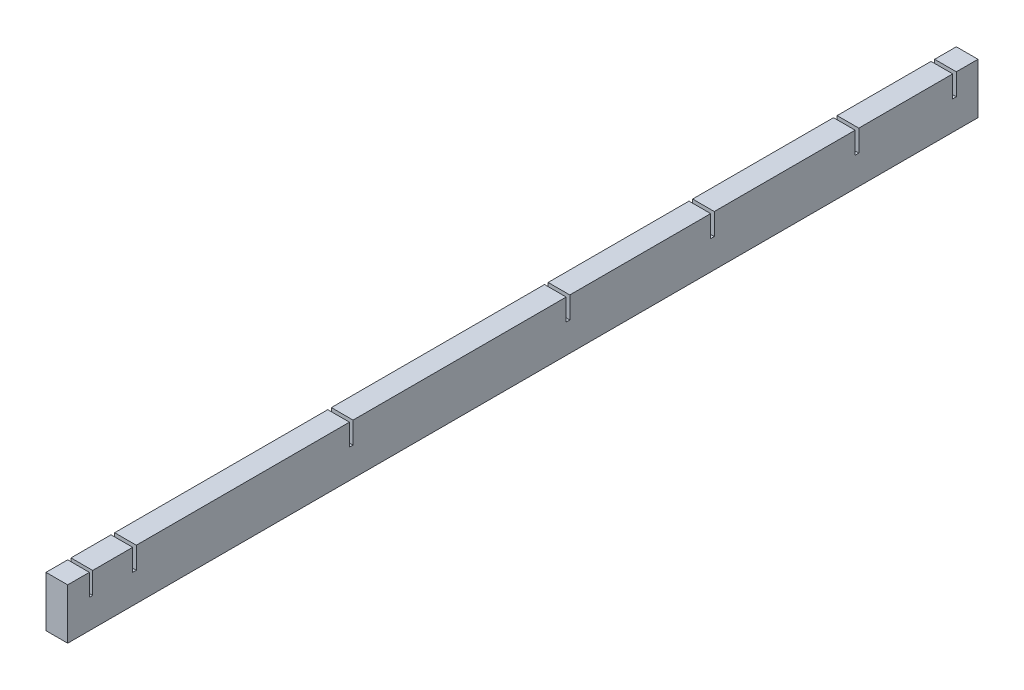
SolidWorks part; units mm, degrees
ref_plane "Front" through (0, 0, 0) normal (0, 0, 1) x (1, 0, 0)
ref_plane "Top" through (0, 0, 0) normal (0, 1, 0) x (1, 0, 0)
ref_plane "Right" through (0, 0, 0) normal (1, 0, 0) x (0, 0, -1)
sketch "Sketch1" plane through (0, 0, 0) normal (0, 0, 1) x (1, 0, 0)
  line L1 (-19.05, 39.6875) -> (19.05, 39.6875)
  line L2 (-19.05, 39.6875) -> (-19.05, 128.5875)
  line L3 (-19.05, 128.5875) -> (19.05, 128.5875)
  line L4 (19.05, 39.6875) -> (19.05, 128.5875)
  line L5 (-19.05, 39.6875) -> (19.05, 128.5875) construction
  line L6 (-19.05, 128.5875) -> (19.05, 39.6875) construction
  point P0 (0, 84.1375)
  dimension "D1" = 38.1
  dimension "D2" = 88.9
  dimension "D3" = 39.6875
extrude "Boss-Extrude1" add sketch "Sketch1" along normal blind 1384.3 and the other way blind 215.9
sketch "Sketch2" plane through (19.05, 0, 0) normal (1, 0, 0) x (0, 0, -1)
  line L0 (215.9, 128.5875) -> (-1384.3, 128.5875) construction
  line L1 (-1346.2, 128.5875) -> (-1340.358, 128.5875)
  line L2 (-1346.2, 128.5875) -> (-1346.2, 90.4875)
  line L3 (-1346.2, 90.4875) -> (-1340.358, 90.4875)
  line L4 (-1340.358, 128.5875) -> (-1340.358, 90.4875)
  line L6 (-1270, 128.5875) -> (-1263.65, 128.5875)
  line L7 (-1270, 128.5875) -> (-1270, 90.4875)
  line L8 (-1270, 90.4875) -> (-1263.65, 90.4875)
  line L9 (-1263.65, 128.5875) -> (-1263.65, 90.4875)
  line L10 (-889, 128.5875) -> (-882.65, 128.5875)
  line L11 (-889, 128.5875) -> (-889, 90.4875)
  line L12 (-889, 90.4875) -> (-882.65, 90.4875)
  line L13 (-882.65, 128.5875) -> (-882.65, 90.4875)
  line L14 (-508, 128.5875) -> (-501.65, 128.5875)
  line L15 (-508, 128.5875) -> (-508, 90.4875)
  line L16 (-508, 90.4875) -> (-501.65, 90.4875)
  line L17 (-501.65, 128.5875) -> (-501.65, 90.4875)
  line L18 (-254, 128.5875) -> (-247.65, 128.5875)
  line L19 (-254, 128.5875) -> (-254, 90.4875)
  line L20 (-254, 90.4875) -> (-247.65, 90.4875)
  line L21 (-247.65, 128.5875) -> (-247.65, 90.4875)
  line L22 (0, 128.5875) -> (6.35, 128.5875)
  line L23 (0, 128.5875) -> (0, 90.4875)
  line L24 (0, 90.4875) -> (6.35, 90.4875)
  line L25 (6.35, 128.5875) -> (6.35, 90.4875)
  line L26 (177.8, 128.5875) -> (171.45, 128.5875)
  line L27 (177.8, 128.5875) -> (177.8, 90.4875)
  line L28 (177.8, 90.4875) -> (171.45, 90.4875)
  line L29 (171.45, 128.5875) -> (171.45, 90.4875)
  dimension "D1" = 38.1
  dimension "D2" = 1346.2
  dimension "D3" = 5.842
  dimension "D4" = 38.1
  dimension "D5" = 6.35
  dimension "D6" = 1270
  dimension "D7" = 38.1
  dimension "D8" = 6.35
  dimension "D9" = 889
  dimension "D10" = 38.1
  dimension "D11" = 6.35
  dimension "D12" = 508
  dimension "D13" = 38.1
  dimension "D14" = 6.35
  dimension "D15" = 254
  dimension "D16" = 38.1
  dimension "D17" = 6.35
  dimension "D18" = 177.8
  dimension "D19" = 6.35
  dimension "D20" = 38.1
extrude "Cut-Extrude1" cut sketch "Sketch2" against normal through all
